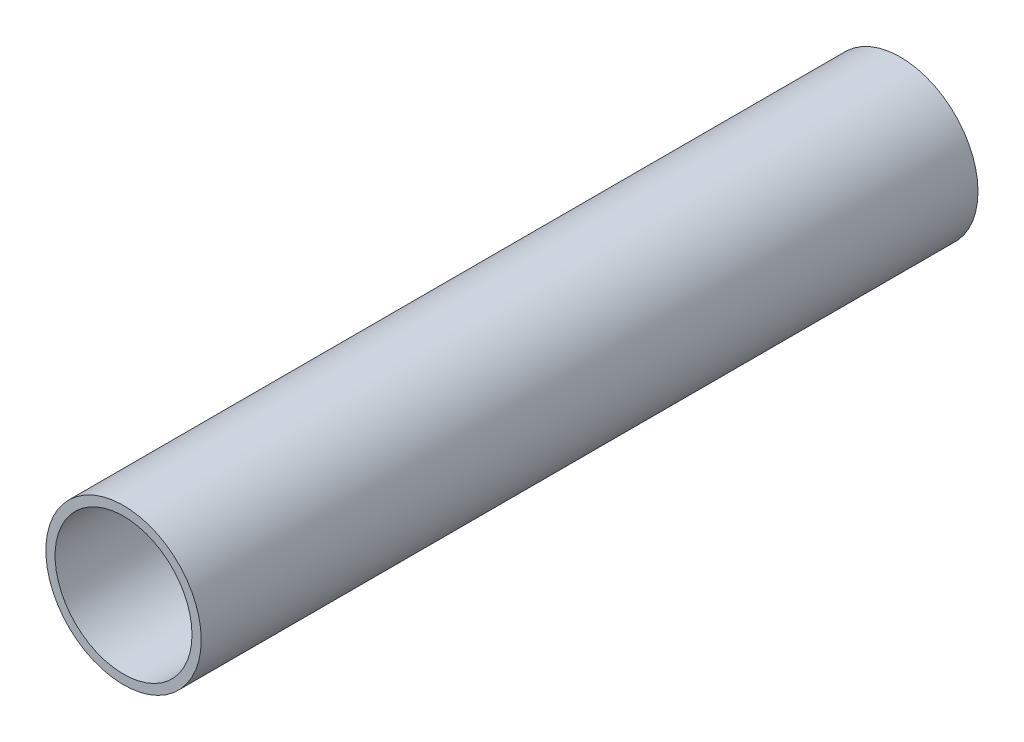
SolidWorks part; units mm, degrees
material "PE Высокой плотности"
ref_plane "Front" through (0, 0, 0) normal (0, 0, 1) x (1, 0, 0)
ref_plane "Top" through (0, 0, 0) normal (0, 1, 0) x (1, 0, 0)
ref_plane "Side" through (0, 0, 0) normal (1, 0, 0) x (0, 0, -1)
sketch "PipeSketch" plane through (0, 0, 0) normal (0, 0, 1) x (1, 0, 0)
  circle A0 centre (0, 0) radius 16
  circle A1 centre (0, 0) radius 14.1
  dimension "OuterDiameter" = 32
  dimension "InnerDiameter" = 28.2
extrude "Extrusion" add sketch "PipeSketch" along normal blind 160
sketch "FilterSketch" plane through (0, 0, 0) normal (0, 0, 1) x (1, 0, 0)
  circle A0 centre (0, 0) radius 16 construction
  dimension "NominalDiameter" = 32
